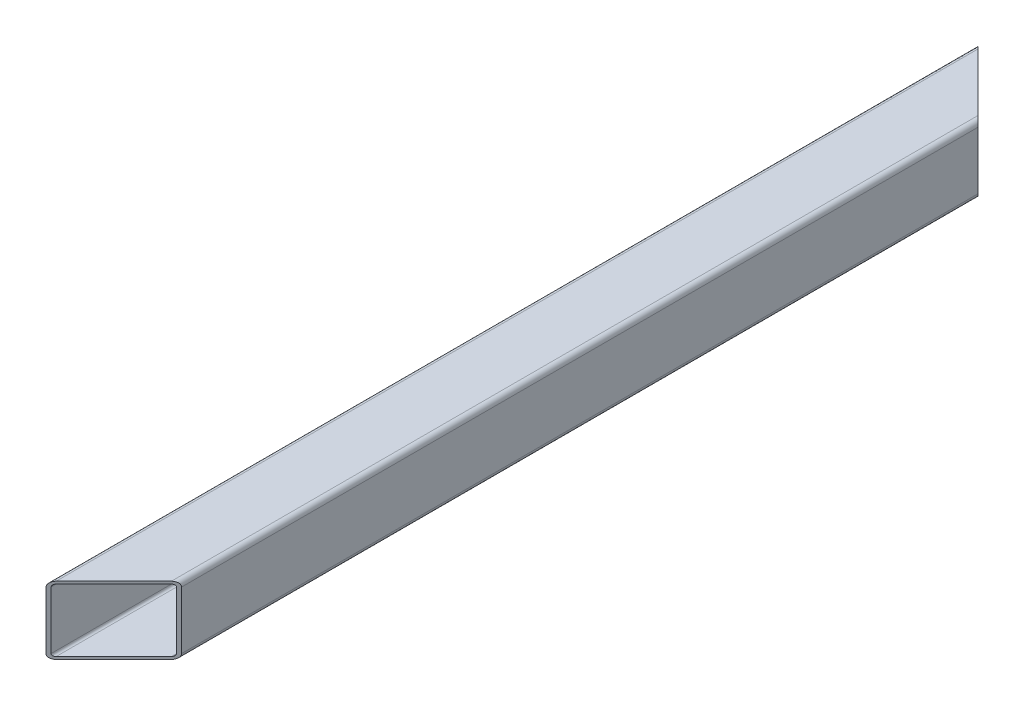
SolidWorks part; units mm, degrees
material "1.0038 (S235JRG2)"
ref_plane "Ebene vorne" through (0, 0, 0) normal (0, 0, 1) x (1, 0, 0)
ref_plane "Ebene oben" through (0, 0, 0) normal (0, 1, 0) x (1, 0, 0)
ref_plane "Ebene rechts" through (0, 0, 0) normal (1, 0, 0) x (0, 0, -1)
sketch "Skizze1" plane through (0, 0, 0) normal (0, 0, 1) x (1, 0, 0)
  line L0 (0, 0) -> (0, 67.8952) construction
  line L1 (-34, 40) -> (34, 40)
  line L2 (0, 0) -> (65.406, 0) construction
  line L3 (40, 34) -> (40, -34)
  line L4 (-40, 34) -> (-40, -34)
  line L5 (-34, -40) -> (34, -40)
  line L6 (-37, 34) -> (-37, -34)
  line L7 (-34, -37) -> (34, -37)
  line L8 (37, 34) -> (37, -34)
  line L9 (-34, 37) -> (34, 37)
  arc A0 (34, 40) -> (40, 34) centre (34, 34) cw
  arc A1 (-34, 40) -> (-40, 34) centre (-34, 34) ccw
  arc A2 (-34, -40) -> (-40, -34) centre (-34, -34) cw
  arc A3 (34, -40) -> (40, -34) centre (34, -34) ccw
  arc A4 (-34, -37) -> (-37, -34) centre (-34, -34) cw
  arc A5 (34, -37) -> (37, -34) centre (34, -34) ccw
  arc A6 (34, 37) -> (37, 34) centre (34, 34) cw
  arc A7 (-34, 37) -> (-37, 34) centre (-34, 34) ccw
  point P12 (40, 0)
  point P13 (0, 40)
  point P19 (-40, 0)
  dimension "D1" = 6
  dimension "D3" = 80
  dimension "D4" = 80
  dimension "D2" = 3
extrude "Aufsatz-Linear austragen1" add sketch "Skizze1" along normal mid plane 1100
sketch "Skizze2" plane through (0, 40, 0) normal (0, 1, 0) x (1, 0, 0)
  line L0 (0, 0) -> (203.443, 0) construction
  line L1 (-40, 550) -> (40, 550)
  line L2 (40, 550) -> (40, 470)
  line L3 (40, 470) -> (-40, 550)
  line L4 (34, 550) -> (-34, 550) construction
  line L5 (-40, -550) -> (-40, 550) construction
  line L6 (40, -550) -> (40, 550) construction
  line L7 (40, -470) -> (-40, -550)
  line L8 (40, -550) -> (40, -470)
  line L9 (-40, -550) -> (40, -550)
  dimension "D1" = 45
extrude "Schnitt-Linear austragen1" cut sketch "Skizze2" against normal blind 140
